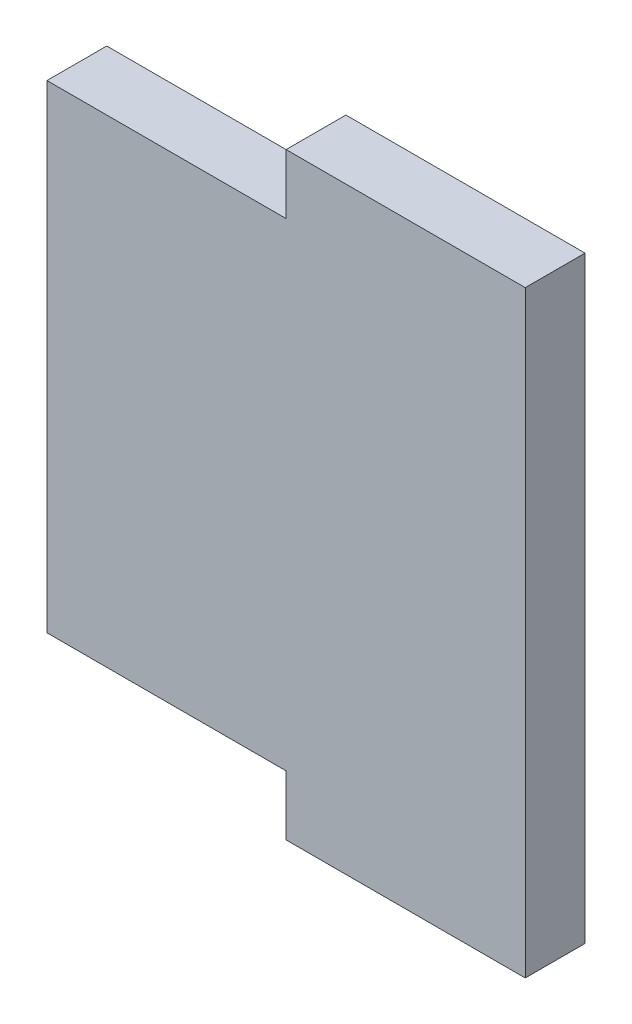
SolidWorks part; units mm, degrees
ref_plane "Front Plane" through (0, 0, 0) normal (0, 0, 1) x (1, 0, 0)
ref_plane "Top Plane" through (0, 0, 0) normal (0, 1, 0) x (1, 0, 0)
ref_plane "Right Plane" through (0, 0, 0) normal (1, 0, 0) x (0, 0, -1)
sketch "Sketch1" plane through (0, 0, 0) normal (0, 0, 1) x (1, 0, 0)
  line L1 (212.725, 0) -> (200.025, 0)
  line L2 (212.725, 0) -> (212.725, -31.75)
  line L3 (212.725, -31.75) -> (200.025, -31.75)
  line L4 (187.325, -3.175) -> (187.325, -28.575)
  line L7 (187.325, -3.175) -> (200.025, -3.175)
  line L8 (200.025, 0) -> (200.025, -3.175)
  line L11 (187.325, -28.575) -> (200.025, -28.575)
  line L12 (200.025, -31.75) -> (200.025, -28.575)
extrude "Boss-Extrude1" add sketch "Sketch1" along normal blind 3.175 contours L2 L3 L12 L11 L4 L7 L8 L1
